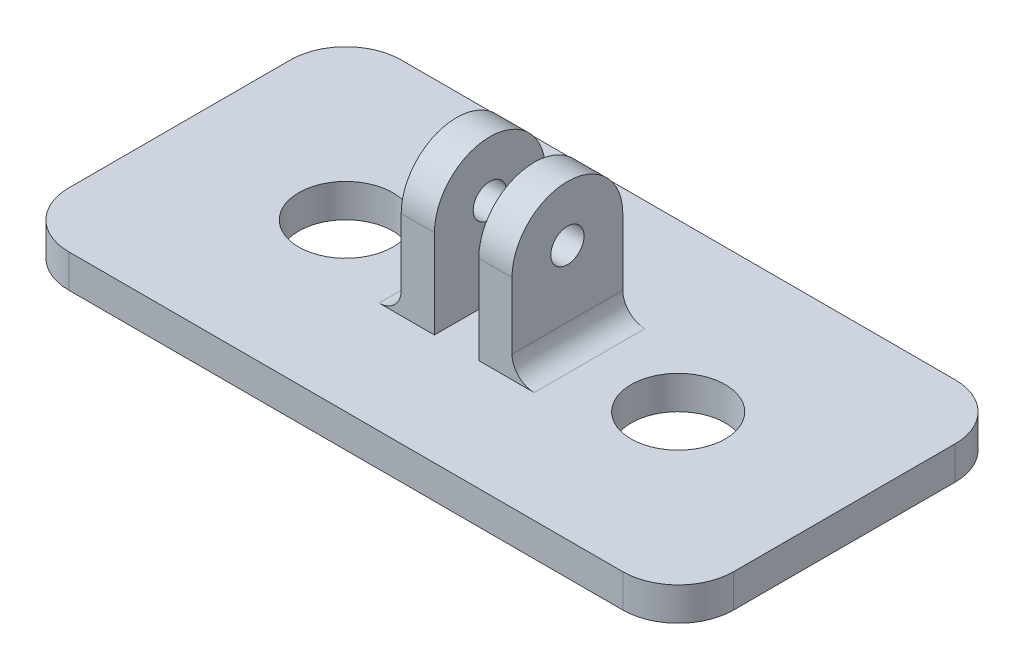
SolidWorks part; units mm, degrees
ref_plane "Alzado" through (0, 0, 0) normal (0, 0, 1) x (1, 0, 0)
ref_plane "Planta" through (0, 0, 0) normal (0, 1, 0) x (1, 0, 0)
ref_plane "Vista lateral" through (0, 0, 0) normal (1, 0, 0) x (0, 0, -1)
sketch "Croquis1" plane through (0, 0, 0) normal (0, 1, 0) x (1, 0, 0)
  line L1 (-30, 15) -> (30, 15)
  line L2 (-30, 15) -> (-30, -15)
  line L3 (-30, -15) -> (30, -15)
  line L4 (30, 15) -> (30, -15)
  line L5 (-30, 15) -> (30, -15) construction
  line L6 (-30, -15) -> (30, 15) construction
  point P0 (0, 0)
extrude "Saliente-Extruir1" add sketch "Croquis1" along normal blind 3
sketch "Croquis2" plane through (0, 3, 0) normal (0, 1, 0) x (1, 0, 0)
  circle A0 centre (-15, 0) radius 4.25
  circle A1 centre (15, 0) radius 4.25
  dimension "D1" = 15
  dimension "D2" = 15
extrude "Cortar-Extruir1" cut sketch "Croquis2" against normal blind 3
fillet "Redondeo1" radius 5 4 edges at (-30, 1.5, -15) (30, 1.5, -15) (30, 1.5, 15) (-30, 1.5, 15)
sketch "Croquis4" plane through (0, 3, 0) normal (0, 1, 0) x (1, 0, 0)
  line L1 (-5, 5) -> (-2, 5)
  line L2 (-5, 5) -> (-5, -5)
  line L3 (-5, -5) -> (-2, -5)
  line L4 (-2, 5) -> (-2, -5)
  line L5 (-5, 5) -> (-2, -5) construction
  line L6 (-5, -5) -> (-2, 5) construction
  line L7 (2, 5) -> (5, 5)
  line L8 (2, 5) -> (2, -5)
  line L9 (2, -5) -> (5, -5)
  line L10 (5, 5) -> (5, -5)
  line L11 (2, 5) -> (5, -5) construction
  line L12 (2, -5) -> (5, 5) construction
  point P0 (-3.5, 0)
  point P5 (3.5, 0)
  dimension "D1" = 3.5
  dimension "D2" = 3.5
extrude "Saliente-Extruir2" add sketch "Croquis4" along normal blind 13
sketch "Croquis5" plane through (5, 0, 0) normal (1, 0, 0) x (0, 0, -1)
  line L0 (-5, 16) -> (5, 16) construction
  line L1 (-5, 11) -> (-5, 16)
  line L2 (-5, 16) -> (5, 16)
  line L3 (5, 16) -> (5, 11)
  circle A0 centre (0, 11) radius 5
  line M2 (5, 3) -> (5, 16)
  line M3 (5, 16) -> (-5, 16)
  line M4 (-5, 16) -> (-5, 3)
  dimension "D1" = 5
extrude "Cortar-Extruir2" cut sketch "Croquis5" against normal blind 13 contours A0 L2 M4 | A0 M2 M3
sketch "Croquis6" plane through (-5, 0, 0) normal (-1, 0, 0) x (0, 0, 1)
  circle A0 centre (0, 11) radius 1.5
extrude "Cortar-Extruir3" cut sketch "Croquis6" against normal blind 13
sketch "Croquis7" plane through (0, 0, 5) normal (0, 0, 1) x (1, 0, 0)
  line L0 (-5, 3) -> (-5, 5) construction
  line L1 (-5, 11) -> (-5, 3) construction
  line L2 (-5, 5) -> (-7, 5) construction
  line L3 (-7, 3) -> (-5, 3)
  line L4 (-5, 3) -> (-5, 5)
  line L5 (5, 3) -> (7, 3) construction
  line L6 (7, 3) -> (7, 5) construction
  line L7 (5, 11) -> (5, 3) construction
  line L8 (5, 5) -> (5, 3)
  line L9 (5, 3) -> (7, 3)
  arc A0 (-5, 5) -> (-7, 3) centre (-7, 5) cw
  arc A1 (7, 3) -> (5, 5) centre (7, 5) cw
extrude "Saliente-Extruir3" add sketch "Croquis7" against normal blind 10
